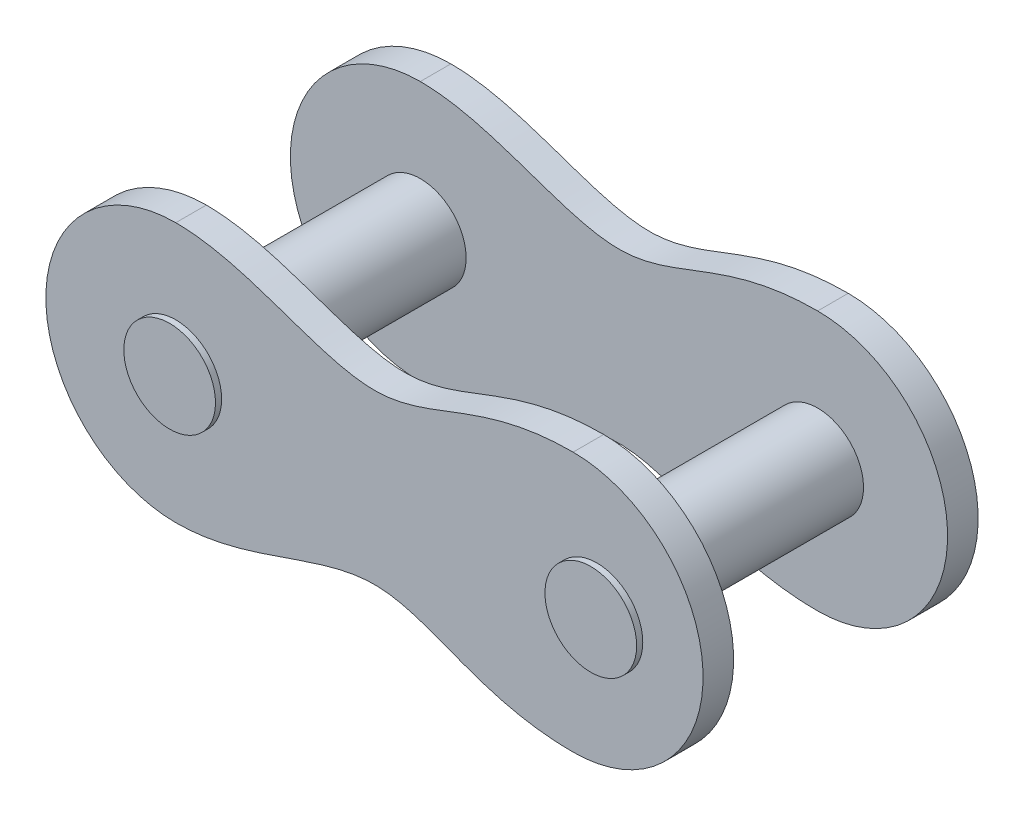
SolidWorks part; units mm, degrees
ref_plane "Front Plane" through (0, 0, 0) normal (0, 0, 1) x (1, 0, 0)
ref_plane "Top Plane" through (0, 0, 0) normal (0, 1, 0) x (1, 0, 0)
ref_plane "Right Plane" through (0, 0, 0) normal (1, 0, 0) x (0, 0, -1)
sketch "Sketch1" plane through (0, 0, 0) normal (0, 0, 1) x (1, 0, 0)
  circle A0 centre (0, 0) radius 1.5
  circle A1 centre (13, 0) radius 1.5
  dimension "D1" = 3
  dimension "D2" = 13
extrude "Boss-Extrude6" add sketch "Sketch1" along normal blind 9
sketch "Sketch5" plane through (0, 0, 9) normal (0, 0, 1) x (1, 0, 0)
  arc A0 (0, 4.25) -> (0, -4.25) centre (0, 0) ccw
  arc A1 (13, -4.25) -> (13, 4.25) centre (13, 0) ccw
  spline S0 degree 3 poles (0, 4.25) (2.3863, 4.25) (6.8636, 1.25) (9.8864, 4.25) (13, 4.25) knots 0 0 0 0 0.5 1 1 1 1
  spline S1 degree 3 poles (0, -4.25) (2.3863, -4.25) (6.8636, -1.25) (9.8864, -4.25) (13, -4.25) knots 0 0 0 0 0.5 1 1 1 1
  dimension "D2" = 8.5
  dimension "D1" = 13
extrude "Boss-Extrude7" add sketch "Sketch5" along normal blind 1
sketch "Sketch6" plane through (0, 0, 10) normal (0, 0, 1) x (1, 0, 0)
  circle A0 centre (0, 0) radius 1.5
  circle A1 centre (13.7777, 0) radius 1.5
  dimension "D1" = 3
extrude "Boss-Extrude8" add sketch "Sketch6" along normal blind 0.2
sketch "Sketch8" plane through (0, 0, 0) normal (1, 0, 0) x (0, 0, -1)
  line L0 (-9, 0) -> (0, 0) construction
  line L1 (-9, -1.5) -> (-9, 1.5) construction
  line L2 (0, 0) -> (0, 2.4183)
  line L3 (0, 2.4183) -> (-2, 2.4183)
  line L4 (-2, 2.4183) -> (-2, -2.3018)
  line L5 (-2, -2.3018) -> (0, -2.3018)
  line L6 (0, -2.3018) -> (0, 0)
  dimension "D1" = 2
extrude "Cut-Extrude1" cut sketch "Sketch8" against normal through all and the other way through all
ref_plane "Plane1" through (0, 0, 5.5) normal (0, 0, -1) x (-1, 0, 0)
mirror "Mirror1" about plane through (0, 0, 5.5) normal (0, 0, -1) of "Boss-Extrude8", "Boss-Extrude7"
